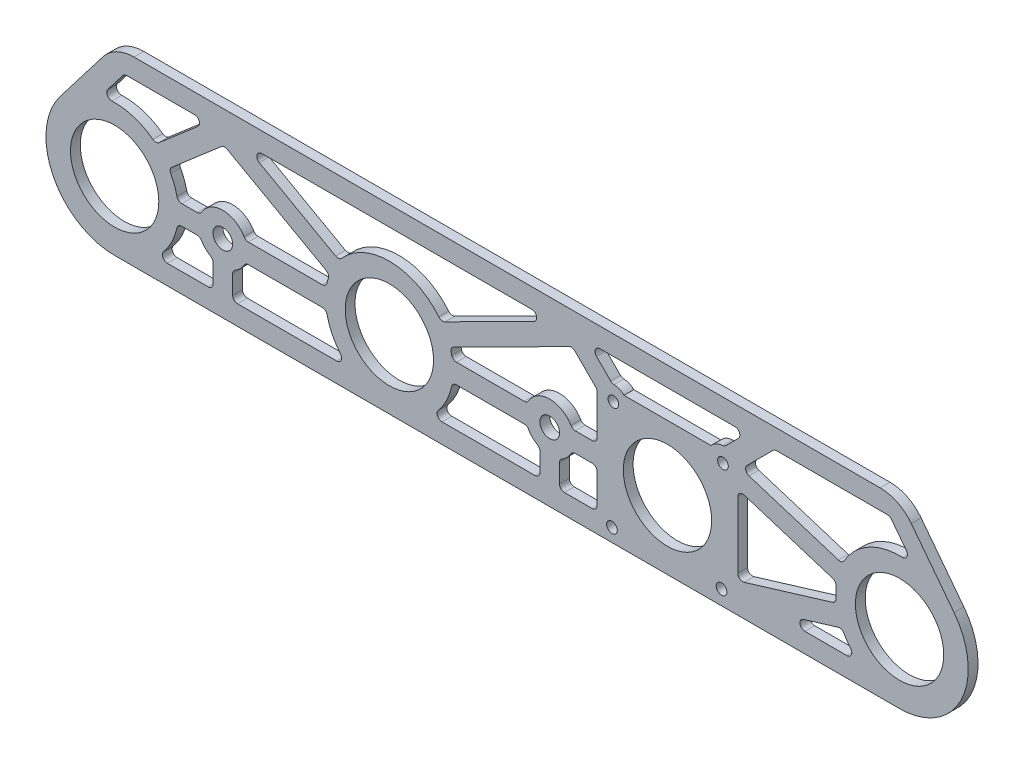
SolidWorks part; units mm, degrees
ref_plane "Front Plane" through (0, 0, 0) normal (0, 0, 1) x (1, 0, 0)
ref_plane "Top Plane" through (0, 0, 0) normal (0, 1, 0) x (1, 0, 0)
ref_plane "Right Plane" through (0, 0, 0) normal (1, 0, 0) x (0, 0, -1)
sketch "Sketch1" plane through (0, 0, 0) normal (0, 0, 1) x (1, 0, 0)
  line L0 (-127, 0) -> (127, 0) construction
  line L1 (-127, 22.225) -> (127, 22.225)
  line L2 (-127, -22.225) -> (127, -22.225)
  line L3 (127, 36.5125) -> (-127, 36.5125)
  line L4 (127, 36.5125) -> (144.6334, 13.5283)
  line L5 (-127, 36.5125) -> (-144.6334, 13.5283)
  circle A0 centre (-127, 0) radius 14.2938
  arc A1 (-127, 22.225) -> (-127, -22.225) centre (-127, 0) ccw
  circle A2 centre (127, 0) radius 14.2938
  arc A3 (127, -22.225) -> (127, 22.225) centre (127, 0) ccw
  circle A4 centre (-38.1, 0) radius 14.2938
  circle A5 centre (127, 0) radius 36.5125 construction
  circle A6 centre (-38.1, 0) radius 36.5125 construction
  circle A8 centre (-88.9, 0) radius 6.35 construction
  point P4 (0, 0)
  point P21 (0, 36.5125)
  dimension "D1" = 73.025
  dimension "D2" = 38.1
  dimension "D3" = 28.5877
  dimension "D4" = 28.5877
  dimension "D5" = 28.5877
  dimension "D6" = 22.225
  dimension "D7" = 254
  dimension "D9" = 73.025
  dimension "D8" = 88.9
  dimension "D10" = 254
extrude "Boss-Extrude2" add sketch "Sketch1" along normal blind 3.175
sketch "Sketch4" plane through (0, 0, 0) normal (0, 0, 1) x (1, 0, 0)
  line L0 (-7.8072, -12.8507) -> (5.7863, 10.694)
  line L1 (-68.7672, -12.8507) -> (-55.1737, 10.694)
  line L2 (-55.1737, 10.694) -> (-82.3608, 10.694)
  line L3 (-82.3608, 10.694) -> (-68.7672, -12.8507)
  line L4 (5.7863, 10.694) -> (-21.4008, 10.694)
  line L5 (-21.4008, 10.694) -> (-7.8072, -12.8507)
  line L6 (96.3328, -12.8507) -> (109.9263, 10.694)
  line L7 (109.9263, 10.694) -> (82.7392, 10.694)
  line L8 (82.7392, 10.694) -> (96.3328, -12.8507)
  circle A0 centre (-68.7672, 2.8458) radius 7.8482 construction
  dimension "D1" = 2
  dimension "D2" = 2
extrude "Cut-Extrude5" [suppressed] cut sketch "Sketch4" along normal through all
fillet "Fillet3" [suppressed] radius 2.54
sketch "Sketch5" plane through (0, 0, 3.175) normal (0, 0, 1) x (1, 0, 0)
  line L0 (-38.1, 19.1008) -> (51.8931, 19.1008) construction
  line L1 (-38.1, -19.1008) -> (51.8931, -19.1008) construction
  arc A0 (51.8931, -19.1008) -> (51.8931, 19.1008) centre (51.8931, 0) ccw construction
  arc A1 (-38.1, 19.1008) -> (-38.1, -19.1008) centre (-38.1, 0) ccw construction
  circle A2 centre (51.8931, 0) radius 14.2939
  dimension "D1" = 38.2016
  dimension "D2" = 300
  dimension "D3" = 28.5877
extrude "Cut-Extrude6" cut sketch "Sketch5" against normal through all
hole_wizard "#8-32 Tapped Hole1" positions "Sketch8" profile "Sketch7" tap size "#8-32" standard "ANSI Inch" end condition up to next
sketch "Sketch8" plane through (0, 0, 3.175) normal (0, 0, 1) x (1, 0, 0)
  point P0 (69.8536, 17.9605)
  point P3 (34.3931, 17.5)
  point P6 (33.9326, -17.9605)
  point P9 (69.3931, -17.5)
sketch "Sketch7" plane through (69.8536, 17.9605, 3.175) normal (1, 0, 0) x (0, -1, 0)
  line L0 (0, 0) -> (0, 3.175)
  line L1 (0, 3.175) -> (1.7272, 3.175)
  line L2 (1.7272, 3.175) -> (1.7272, 0)
  line L5 (1.7272, 0) -> (0, 0)
  line L11 (0, -6.35) -> (0, 107.95) construction
  dimension "Thru Tap Drill Dia." = 3.4544
  dimension "Thru Tap Drill Depth" = 3.175
cosmetic thread "Hole Thread5" parameters "D1"=3.175, "D2"=4.1656
cosmetic thread "Hole Thread6" parameters "D1"=3.175, "D2"=4.1656
cosmetic thread "Hole Thread7" parameters "D1"=3.175, "D2"=4.1656
cosmetic thread "Hole Thread8" parameters "D1"=3.175, "D2"=4.1656
hole_wizard "1/4 (0.25) Diameter Hole1" positions "Sketch9" profile "Sketch10" hole size "1/4" standard "ANSI Inch" end condition up to next
sketch "Sketch9" plane through (0, 0, 3.175) normal (0, 0, 1) x (1, 0, 0)
  line L0 (13.7931, 0) -> (13.7931, 28.2575) construction
  circle A0 centre (51.8931, 0) radius 14.2939 construction
  point P0 (-91.9903, 0)
  point P2 (13.7931, 0)
  point P27 (0, 0)
  point P28 (0, 0)
  point P29 (81.3133, 28.2575)
  dimension "D1" = 31.75
  dimension "D4" = 38.1
sketch "Sketch10" plane through (-91.9903, 0, 3.175) normal (1, 0, 0) x (0, -1, 0)
  line L0 (0, 0) -> (0, 3.175)
  line L1 (0, 3.175) -> (3.175, 3.175)
  line L2 (3.175, 3.175) -> (3.175, 0)
  line L5 (3.175, 0) -> (0, 0)
  line L11 (0, -6.35) -> (0, 107.95) construction
  dimension "Thru Hole Dia." = 6.35
  dimension "Thru Hole Depth" = 3.175
sketch "Sketch11" plane through (0, 0, 3.175) normal (0, 0, 1) x (1, 0, 0)
  line L4 (-113.8033, -15.875) -> (-95.1653, -15.875)
  line L5 (131.5625, 20.1334) -> (123.8682, 30.1625)
  line L6 (123.8682, 30.1625) -> (86.5457, 30.1625)
  line L7 (-123.8682, 30.1625) -> (-131.5625, 20.1334)
  line L16 (144.6334, 13.5283) -> (127, 36.5125)
  line L17 (127, 36.5125) -> (-127, 36.5125)
  line L19 (-127, 36.5125) -> (-144.6334, 13.5283)
  line L24 (-127, -22.225) -> (127, -22.225)
  line L25 (144.6334, 13.5283) -> (127, 36.5125)
  line L26 (127, 36.5125) -> (-127, 36.5125)
  line L27 (-127, 36.5125) -> (-144.6334, 13.5283)
  line L28 (-127, -22.225) -> (127, -22.225)
  line L29 (127, 0) -> (69.3931, -17.5) construction
  line L30 (127, 0) -> (69.8536, 17.9605) construction
  line L31 (34.3931, 17.5) -> (21.7306, 30.1625) construction
  line L32 (69.8536, 17.9605) -> (82.0556, 30.1625) construction
  line L33 (51.8931, 0) -> (13.7931, 0) construction
  line L37 (13.7931, 0) -> (-38.1, 0) construction
  line L52 (-38.1, 0) -> (-91.9903, 0) construction
  line L53 (-91.9903, 0) -> (-127, 0) construction
  line L55 (21.7306, 30.1625) -> (-38.1, 0) construction
  line L57 (-38.1, 0) -> (-91.9903, 30.1625) construction
  line L58 (-91.9903, 30.1625) -> (-127, 0) construction
  line L59 (106.5883, 3.0871) -> (74.6431, 13.1271)
  line L60 (106.5596, -2.8912) -> (74.6431, -12.5869)
  line L61 (33.997, 22.3862) -> (26.2207, 30.1625)
  line L62 (14.6776, 30.1625) -> (-21.3147, 12.0176)
  line L63 (29.1431, 3.175) -> (21.0679, 3.175)
  line L64 (6.5182, 3.175) -> (-17.7018, 3.175)
  line L69 (-96.8546, 30.1625) -> (-113.6186, 15.7196)
  line L70 (-99.2652, -3.175) -> (-106.6018, -3.175)
  line L75 (75.8022, 19.419) -> (86.5457, 30.1625)
  line L77 (108.4922, 9.1449) -> (75.8022, 19.419)
  line L78 (108.4053, -8.967) -> (85.6654, -15.875)
  line L79 (29.1431, 18.2599) -> (21.1093, 26.2936)
  line L82 (21.1093, 26.2936) -> (-18.4562, 6.3474)
  line L84 (29.1431, -3.175) -> (21.0679, -3.175)
  line L85 (6.5182, -3.175) -> (-17.7018, -3.175)
  line L86 (-57.4505, 7.192) -> (-91.6017, 26.3065)
  line L88 (-91.6017, 26.3065) -> (-109.4738, 10.9088)
  line L93 (-99.2652, 3.175) -> (-106.6018, 3.175)
  line L94 (-58.4982, 3.175) -> (-84.7155, 3.175)
  line L96 (-127, -15.875) -> (127, -15.875) construction
  line L98 (137.7534, -0.0516) -> (70.3159, -20.5379) construction
  line L99 (137.7534, -0.0516) -> (75.8022, 19.419) construction
  line L101 (139.5953, 9.663) -> (123.8682, 30.1625) construction
  line L105 (116.2466, 0.0516) -> (63.9049, 16.502) construction
  line L106 (116.2466, 0.0516) -> (68.4702, -14.4621) construction
  line L112 (70.2496, 22.8467) -> (77.5654, 30.1625)
  line L113 (85.6654, -15.875) -> (113.8033, -15.875)
  line L114 (63.9049, 16.502) -> (79.7769, 32.374) construction
  line L115 (75.8022, 19.419) -> (84.267, 27.8838) construction
  line L116 (69.8536, 17.9605) -> (82.022, 30.1289) construction
  line L117 (77.5654, 30.1625) -> (26.2207, 30.1625)
  line L118 (123.8682, 30.1625) -> (-123.8682, 30.1625) construction
  line L119 (36.6381, 19.7451) -> (22.3518, 34.0314) construction
  line L120 (32.148, 15.2549) -> (21.1093, 26.2936) construction
  line L121 (22.3518, 34.0314) -> (-39.5293, 2.8351) construction
  line L122 (14.6776, 30.1625) -> (-85.4896, 30.1625)
  line L123 (-58.4982, -3.175) -> (-84.7155, -3.175)
  line L124 (13.7931, 3.175) -> (-38.1, 3.175) construction
  line L125 (-50.2734, 3.175) -> (-91.6017, 26.3065) construction
  line L126 (21.1093, 26.2936) -> (-36.6707, -2.8351) construction
  line L127 (-25.9266, -3.175) -> (-91.9903, -3.175) construction
  line L129 (-54.3492, 12.7332) -> (-85.4896, 30.1625)
  line L130 (-25.9266, -3.175) -> (-92.379, 34.0185) construction
  line L131 (13.7931, -3.175) -> (-38.1, -3.175) construction
  line L132 (-50.2734, 3.175) -> (-91.9903, 3.175) construction
  line L133 (-92.379, 34.0185) -> (-135.5495, -3.175) construction
  line L134 (-96.8546, 30.1625) -> (-123.8682, 30.1625)
  line L135 (-91.6017, 26.3065) -> (-118.4505, 3.175) construction
  line L136 (-91.9903, 3.175) -> (-118.4505, 3.175) construction
  line L137 (-91.9903, -3.175) -> (-135.5495, -3.175) construction
  line L138 (-123.8682, 30.1625) -> (-139.5953, 9.663) construction
  line L139 (51.8931, -3.175) -> (13.7931, -3.175) construction
  line L140 (51.8931, 3.175) -> (13.7931, 3.175) construction
  line L141 (-24.9033, -15.875) -> (10.6181, -15.875)
  line L142 (66.0074, 21) -> (29.1431, 21)
  line L144 (74.6431, 13.1271) -> (74.6431, -12.5869)
  line L146 (29.1431, 21) -> (29.1431, -15.875)
  line L147 (-91.9903, 0) -> (-91.9903, -15.875) construction
  line L148 (-95.1653, -7.2748) -> (-95.1653, -15.875)
  line L149 (-88.8153, -7.2748) -> (-88.8153, -15.875)
  line L150 (-88.8153, -15.875) -> (-51.2967, -15.875)
  line L151 (-88.8153, 0) -> (-88.8153, -15.875) construction
  line L152 (-95.1653, 0) -> (-95.1653, -15.875) construction
  line L153 (13.7931, 0) -> (13.7931, -15.875) construction
  line L154 (10.6181, -7.2748) -> (10.6181, -15.875)
  line L155 (16.9681, -7.2748) -> (16.9681, -15.875)
  line L156 (16.9681, -15.875) -> (29.1431, -15.875)
  line L157 (16.9681, 0) -> (16.9681, -15.875) construction
  line L158 (10.6181, 0) -> (10.6181, -15.875) construction
  arc A16 (70.2496, 22.8467) -> (66.0074, 21) centre (69.8536, 17.9605) ccw
  circle A17 centre (69.8536, 17.9605) radius 1.7272 construction
  arc A18 (106.5883, 3.0871) -> (106.5596, -2.8912) centre (127, 0) ccw
  arc A21 (-58.4982, -3.175) -> (-51.2967, -15.875) centre (-38.1, 0) ccw
  arc A28 (127, -22.225) -> (144.6334, 13.5283) centre (127, 0) ccw
  arc A44 (-144.6334, 13.5283) -> (-127, -22.225) centre (-127, 0) ccw
  arc A45 (127, -22.225) -> (144.6334, 13.5283) centre (127, 0) ccw
  arc A50 (-21.3147, 12.0176) -> (-54.3492, 12.7332) centre (-38.1, 0) ccw
  arc A54 (-113.8033, -15.875) -> (-106.6018, -3.175) centre (-127, 0) ccw
  arc A57 (-144.6334, 13.5283) -> (-127, -22.225) centre (-127, 0) ccw
  arc A58 (-106.6018, 3.175) -> (-109.4738, 10.9088) centre (-127, 0) ccw
  arc A59 (-84.7155, 3.175) -> (-99.2652, 3.175) centre (-91.9903, 0) ccw
  circle A60 centre (69.3931, -17.5) radius 1.7272 construction
  arc A62 (6.5182, -3.175) -> (10.6181, -7.2748) centre (13.7931, 0) ccw
  arc A63 (-17.7018, 3.175) -> (-18.4562, 6.3474) centre (-38.1, 0) ccw
  arc A64 (-24.9033, -15.875) -> (-17.7018, -3.175) centre (-38.1, 0) ccw
  arc A65 (-88.8153, -7.2748) -> (-84.7155, -3.175) centre (-91.9903, 0) ccw
  arc A66 (16.9681, -7.2748) -> (21.0679, -3.175) centre (13.7931, 0) ccw
  circle A109 centre (127, 0) radius 20.6438
  arc A110 (131.5625, 20.1334) -> (108.4922, 9.1449) centre (127, 0) ccw
  circle A115 centre (-38.1, 0) radius 20.6438
  arc A116 (-57.4505, 7.192) -> (-58.4982, 3.175) centre (-38.1, 0) ccw
  circle A118 centre (-127, 0) radius 20.6438
  arc A119 (-113.6186, 15.7196) -> (-131.5625, 20.1334) centre (-127, 0) ccw
  circle A123 centre (13.7931, 0) radius 7.9375
  arc A124 (21.0679, 3.175) -> (6.5182, 3.175) centre (13.7931, 0) ccw
  circle A126 centre (-91.9903, 0) radius 7.9375
  arc A127 (-99.2652, -3.175) -> (-95.1653, -7.2748) centre (-91.9903, 0) ccw
  arc A137 (108.4053, -8.967) -> (113.8033, -15.875) centre (127, 0) ccw
  circle A138 centre (34.3931, 17.5) radius 4.9022
  arc A139 (37.8255, 21) -> (33.997, 22.3862) centre (34.3931, 17.5) ccw
  arc A140 (127, -15.875) -> (139.5953, 9.663) centre (127, 0) ccw construction
  arc A141 (-139.5953, 9.663) -> (-127, -15.875) centre (-127, 0) ccw construction
  point P49 (33.9326, -17.9605)
  dimension "D1" = 0
  dimension "D2" = 6.35
  dimension "D3" = 6.35
  dimension "D4" = 3.175
  dimension "D5" = 6.35
  dimension "D6" = 6.35
  dimension "D7" = 4.7625
  dimension "D8" = 4.7625
  dimension "D9" = 3.175
  dimension "D10" = 3.175
  dimension "D12" = 3.175
  dimension "D11" = 3.175
  dimension "D15" = 3.175
  dimension "D16" = 3.175
  dimension "D17" = 3.175
  dimension "D13" = 3.175
  dimension "D14" = 3.175
extrude "Cut-Extrude7" cut sketch "Sketch11" against normal through all
fillet "Fillet5" radius 1.5875 58 edges at (-24.9033, -15.875, 1.5875) (6.5182, -3.175, 1.5875) (-17.7018, -3.175, 1.5875) (-58.4982, -3.175, 1.5875) (-113.8033, -15.875, 1.5875) (-99.2652, -3.175, 1.5875) (-106.6018, -3.175, 1.5875) (-131.5625, 20.1334, 1.5875) (-123.8682, 30.1625, 1.5875) (-113.6186, 15.7196, 1.5875) (-96.8546, 30.1625, 1.5875) (-58.4982, 3.175, 1.5875) (-84.7155, 3.175, 1.5875) (-99.2652, 3.175, 1.5875) (-106.6018, 3.175, 1.5875) (-109.4738, 10.9088, 1.5875) (-57.4505, 7.192, 1.5875) (-91.6017, 26.3065, 1.5875) (6.5182, 3.175, 1.5875) (-17.7018, 3.175, 1.5875) (-18.4562, 6.3474, 1.5875) (21.0679, 3.175, 1.5875) (21.1093, 26.2936, 1.5875) (-54.3492, 12.7332, 1.5875) (-85.4896, 30.1625, 1.5875) (-21.3147, 12.0176, 1.5875) (14.6776, 30.1625, 1.5875) (33.997, 22.3862, 1.5875) (26.2207, 30.1625, 1.5875) (70.2496, 22.8467, 1.5875) (77.5654, 30.1625, 1.5875) (108.4922, 9.1449, 1.5875) (75.8022, 19.419, 1.5875) (86.5457, 30.1625, 1.5875) (131.5625, 20.1334, 1.5875) (123.8682, 30.1625, 1.5875) (106.5596, -2.8912, 1.5875) (106.5883, 3.0871, 1.5875) (113.8033, -15.875, 1.5875) (85.6654, -15.875, 1.5875) (108.4053, -8.967, 1.5875) (29.1431, 18.2599, 1.5875) (29.1431, 3.175, 1.5875) (29.1431, -3.175, 1.5875) (74.6431, 13.1271, 1.5875) (74.6431, -12.5869, 1.5875) (-95.1653, -7.2748, 1.5875) (-95.1653, -15.875, 1.5875) (-84.7155, -3.175, 1.5875) (-51.2967, -15.875, 1.5875) (-88.8153, -15.875, 1.5875) (-88.8153, -7.2748, 1.5875) (21.0679, -3.175, 1.5875) (29.1431, -15.875, 1.5875) (16.9681, -7.2748, 1.5875) (16.9681, -15.875, 1.5875) (10.6181, -15.875, 1.5875) (10.6181, -7.2748, 1.5875)
fillet "Fillet6" radius 12.7 2 edges at (-127, 36.5125, 1.5875) (127, 36.5125, 1.5875)
